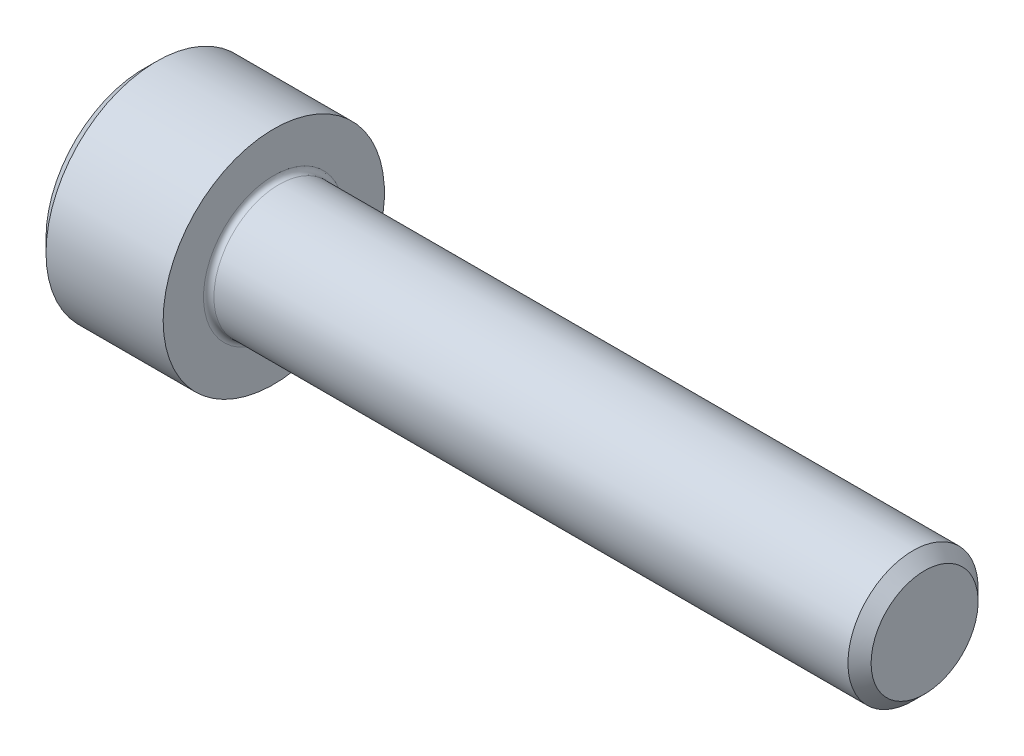
SolidWorks part; units mm, degrees
ref_plane "Plane1" through (0, 0, 0) normal (0, 0, 1) x (1, 0, 0)
ref_plane "Plane2" through (0, 0, 0) normal (0, 1, 0) x (1, 0, 0)
ref_plane "Plane3" through (0, 0, 0) normal (1, 0, 0) x (0, 0, -1)
sketch "BodySke" plane through (0, 0, 0) normal (0, 0, 1) x (1, 0, 0)
  line L0 (0, 0) -> (0, 3.75)
  line L1 (0.5, 4.25) -> (5, 4.25)
  line L2 (5, 4.25) -> (5, 2.5)
  line L3 (5, 2.5) -> (29.555, 2.5)
  line L4 (30, 2.055) -> (30, 0)
  line L5 (30, 0) -> (0, 0)
  line L6 (-31.75, 0) -> (127, 0) construction
  line L7 (0, 3.75) -> (0.5, 4.25)
  line L8 (30, 2.055) -> (29.555, 2.5)
  line L9 (0, -3.75) -> (0.5, -4.25) construction
  line L10 (30, -2.055) -> (29.555, -2.5) construction
  line L11 (5.8, 9.525) -> (5.8, 3.175) construction
  line L12 (5, 9.525) -> (5, 3.175) construction
  line L13 (-20, 9.525) -> (-20, 3.175) construction
  dimension "Diameter" = 5
  dimension "Head_ht" = 5
  dimension "Length" = 25
  dimension "Body_ch_ang" = 45
  dimension "Head_dia" = 8.5
  dimension "Head_ch_ang" = 45
  dimension "Minor_dia" = 4.11
  dimension "Advance" = 0.8
  dimension "Thread_nom" = 25
  dimension "Thread_length" = 50
  dimension "Head_ch_ht" = 0.5
revolve "Base-Revolve" add sketch "BodySke"
cosmetic thread "ThreadCosmetic" [suppressed]
fillet "Fillet1" radius 0.2 1 edges at (5, 0, 2.5)
sketch "Sketch2" plane through (0, 0, 0) normal (0, 0, 1) x (1, 0, 0)
  line L0 (0, 2.042) -> (2.5, 2.042)
  line L1 (2.5, 2.042) -> (3.6789, 0)
  line L2 (-31.75, 0) -> (127, 0) construction
  line L3 (3.6789, 0) -> (0, 0)
  line L4 (0, 0) -> (0, 2.042)
  line L5 (0, 3.75) -> (0, -3.75) construction
  line L6 (0, 0) -> (47.625, 0) construction
  line L7 (5, -4.25) -> (5, 4.25) construction
  dimension "D1" = 2.042
  dimension "D2" = 60
  dimension "Wall_thickness" = 2.5
revolve "Hex-PreBroach" cut sketch "Sketch2" angle 360 about L6
sketch "Sketch3" plane through (0, 0, 0) normal (-1, 0, 0) x (0, 0.5, 0.866)
  line L0 (1.1789, 2.042) -> (-1.1789, 2.042)
  line L1 (-1.1789, 2.042) -> (-2.3579, 0)
  line L2 (1.1789, 2.042) -> (2.3579, 0)
  line L3 (1.1789, -2.042) -> (2.3579, 0)
  line L4 (1.1789, -2.042) -> (-1.1789, -2.042)
  line L5 (-1.1789, -2.042) -> (-2.3579, 0)
  dimension "D1" = 2.042
  dimension "D2" = 2.042
  dimension "Hex_size" = 4.084
extrude "Hex" cut sketch "Sketch3" against normal blind 2.5
sketch "Sketch4" plane through (0, 0, 0) normal (-1, 0, 0) x (0, 0, 1)
  line L0 (0, 0) -> (2.3876, 0)
  line L1 (0, 0) -> (6.1484, 3.5498) construction
  line L2 (0, 0) -> (1.1938, 2.0677)
  line L3 (1.9883, 0.576) -> (2.2704, 0.7389)
  line L4 (1.493, 1.4339) -> (1.7751, 1.5968)
  arc A0 (1.9883, 0.576) -> (1.493, 1.4339) centre (0, 0) ccw
  arc A1 (2.3876, 0) -> (2.2704, 0.7389) centre (0, 0) ccw
  arc A2 (1.1938, 2.0677) -> (1.7751, 1.5968) centre (0, 0) cw
  dimension "D1" = 30
  dimension "Spline_n_dim" = 4.1402
  dimension "Spline_m_dim" = 4.7752
  dimension "D2" = 60
  dimension "D3" = 0.4953
  dimension "Spline_p_dim" = 0.9906
extrude "Spline" [suppressed] cut sketch "Sketch4" against normal blind 2.5
pattern_circular "CirPattern1" [suppressed] count 6 every 60
sketch "Sketch5" plane through (0, 0, 0) normal (0, 0, 1) x (1, 0, 0)
  line L0 (-31.75, 0) -> (127, 0) construction
  line L2 (0, 3.75) -> (0, -3.75) construction
  circle A0 centre (2, 0) radius 0.675
  dimension "Drilled_hole_dia" = 1.35
  dimension "Drilled_hole_loc" = 2
extrude "Hole" [suppressed] cut sketch "Sketch5" against normal through all and the other way through all
pattern_circular "Drilled-4" [suppressed] count 2 every 60
pattern_circular "Drilled-6" [suppressed] count 3 every 60
sketch "ThdSchSke" plane through (0, 0, 0) normal (0, 0, 1) x (1, 0, 0)
  line L0 (5.8, -2.055) -> (5.4884, -2.5)
  line L1 (5.8, -2.055) -> (6.1116, -2.5)
  line L2 (6.1116, -2.5) -> (6.1116, -3.125)
  line L3 (-3.175, 0) -> (5.1513, 0) construction
  line L5 (6.1116, -3.125) -> (5.4884, -3.125)
  line L6 (5.4884, -3.125) -> (5.4884, -2.5)
  line L7 (0, 3.75) -> (0, -3.75) construction
  dimension "Thread_minor" = 4.11
  dimension "Diameter" = 5
  dimension "Start" = 5.8
  dimension "SideAngle" = 55
  dimension "VeeAngle" = 70
  dimension "Overcut" = 6.25
revolve "ThreadSchematic" [suppressed] cut sketch "ThdSchSke" angle 360 about L3
pattern_linear "ThdSchPat" [suppressed]
equation "\"D2@Sketch3\" = \"Hex_size@Sketch3\" / 2"
equation "\"D1@Sketch3\" = \"Hex_size@Sketch3\" / 2"
equation "\"D1@Sketch2\" = \"Hex_size@Sketch3\" / 2"
equation "\"D3@Sketch4\" = \"Spline_p_dim@Sketch4\" / 2"
equation "\"Thread_minor@ThreadCosmetic\"  =  \"Minor_dia@BodySke\""
equation "\"D2@CirPattern1\" = 360 / \"Num_teeth@CirPattern1\""
equation "\"Wall_thickness@Sketch2\" = \"Head_ht@BodySke\" - \"Key_eng@Hex\""
equation "\"Thread_length@ThreadCosmetic\" = ((sgn( (\"Length@BodySke\" - \"Advance@BodySke\" ) - \"Thread_nom@BodySke\" )-1)*( (\"Length@BodySke\" - \"Advance@BodySke\" ) - \"Thread_nom@BodySke\" ))/-2+ \"Thread_nom@BodySke\""
equation "\"Thread_minor@ThdSchSke\" = \"Minor_dia@BodySke\""
equation "\"Diameter@ThdSchSke\" = \"Diameter@BodySke\""
equation "\"Overcut@ThdSchSke\" = \"Diameter@BodySke\" * 1.25"
equation "\"Start@ThdSchSke\" = \"Head_ht@BodySke\" + \"Length@BodySke\" - \"Thread_length@ThreadCosmetic\"  '---Non-countersunk---"
equation "\"Num_threads@ThdSchPat\" = int( \"Thread_length@ThreadCosmetic\" / \"Advance@BodySke\" + 0.999 )  + 1"
equation "\"Advance@ThdSchPat\" = \"Thread_length@ThreadCosmetic\" /  (\"Num_threads@ThdSchPat\" - 1) 'relax it"
equation "\"Num_threads@ThdSchPat\" = \"Num_threads@ThdSchPat\" - sgn( \"Num_threads@ThdSchPat\" - 1) '---chamfered tips only---"
